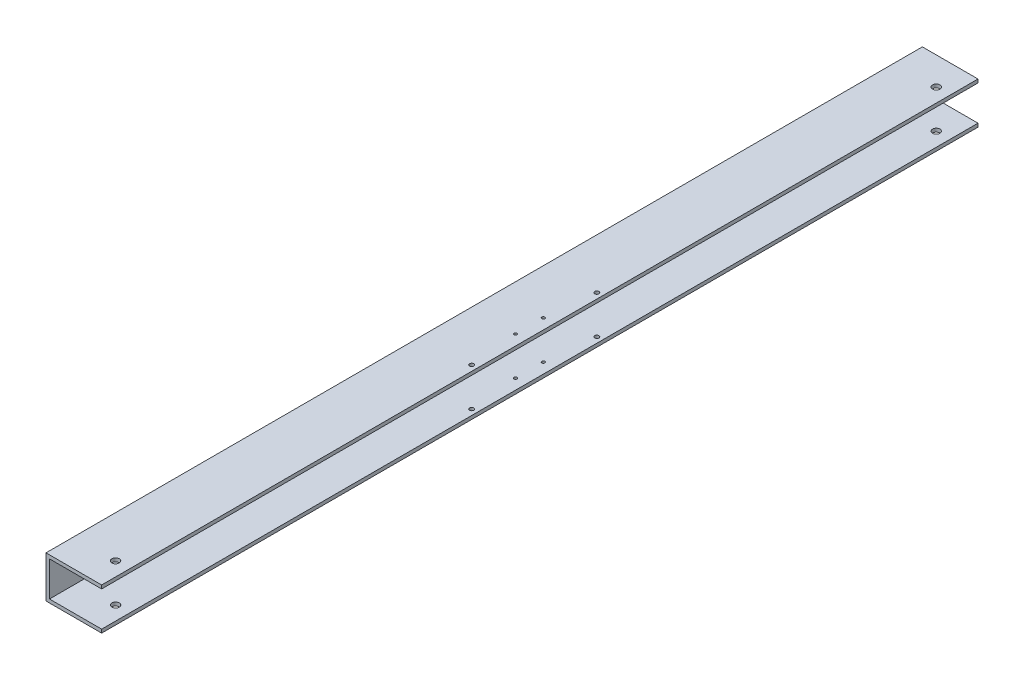
SolidWorks part; units mm, degrees
material "6061 Alloy"
ref_plane "Front Plane" through (0, 0, 0) normal (0, 0, 1) x (1, 0, 0)
ref_plane "Top Plane" through (0, 0, 0) normal (0, 1, 0) x (1, 0, 0)
ref_plane "Right Plane" through (0, 0, 0) normal (1, 0, 0) x (0, 0, -1)
sketch "Sketch1" plane through (0, 0, 0) normal (0, 0, 1) x (1, 0, 0)
  line L0 (-22.225, -15.875) -> (25.4, -15.875)
  line L1 (-25.4, 19.05) -> (25.4, 19.05)
  line L2 (-25.4, 19.05) -> (-25.4, -19.05)
  line L3 (-25.4, -19.05) -> (25.4, -19.05)
  line L4 (-22.225, 15.875) -> (-22.225, -15.875)
  line L5 (-25.4, 19.05) -> (25.4, -19.05) construction
  line L6 (-25.4, -19.05) -> (25.4, 19.05) construction
  line L7 (-22.225, 15.875) -> (25.4, 15.875)
  line L8 (25.4, 19.05) -> (25.4, 15.875)
  line L9 (25.4, -15.875) -> (25.4, -19.05)
  point P0 (0, 0)
  dimension "D1" = 50.8
  dimension "D2" = 38.1
  dimension "D3" = 3.175
extrude "Boss-Extrude1" add sketch "Sketch1" along normal mid plane 800.1
hole_wizard "#6-32 Tapped Hole1" positions "Sketch4" profile "Sketch3" tap size "#6-32" standard "ANSI Inch"
sketch "Sketch4" plane through (0, 19.05, 0) normal (0, 1, 0) x (1, 0, 0)
  line L0 (-25.4, 0) -> (25.4, 0) construction
  line L1 (-25.4, -400.05) -> (-25.4, 400.05) construction
  point P9 (15.875, -12.7)
  dimension "D1" = 12.7
  dimension "D2" = 41.275
sketch "Sketch3" plane through (15.875, 19.05, 12.7) normal (1, 0, 0) x (0, 0, 1)
  line L0 (0, 0) -> (0, 38.9117)
  line L1 (0, 38.9117) -> (1.3525, 38.099)
  line L2 (1.3525, 38.099) -> (1.3525, 0)
  line L5 (1.3525, 0) -> (0, 0)
  line L10 (0, 38.9117) -> (-1.3526, 38.099) construction
  line L11 (0, -6.35) -> (0, 107.95) construction
  dimension "Tap Drill Dia." = 2.7051
  dimension "Tap Drill Depth" = 38.099
  dimension "Drill Angle" = 118
cosmetic thread "Hole Thread1" parameters "D1"=17.272, "D2"=3.5052
hole_wizard "#6 Clearance Hole1" positions "Sketch6" profile "Sketch5" hole size "#6" standard "ANSI Inch"
sketch "Sketch6" plane through (0, 19.05, 0) normal (0, 1, 0) x (1, 0, 0)
  line L0 (25.4, 0) -> (-25.4, 0) construction
  line L1 (25.4, -400.05) -> (25.4, 400.05) construction
  line L2 (-25.4, -400.05) -> (-25.4, 400.05) construction
  point P9 (20.32, -57.15)
  dimension "D1" = 5.08
  dimension "D2" = 57.15
sketch "Sketch5" plane through (20.32, 19.05, 57.15) normal (1, 0, 0) x (0, 0, 1)
  line L0 (0, 0) -> (0, 39.2398)
  line L1 (0, 39.2398) -> (1.8986, 38.099)
  line L2 (1.8986, 38.099) -> (1.8986, 0)
  line L5 (1.8986, 0) -> (0, 0)
  line L10 (0, 39.2398) -> (-1.8987, 38.099) construction
  line L11 (0, -6.35) -> (0, 107.95) construction
  dimension "Hole Dia." = 3.7973
  dimension "Hole Depth" = 38.099
  dimension "Drill Angle" = 118
hole_wizard "1/4 Clearance Hole1" positions "Sketch8" profile "Sketch7" hole size "1/4" standard "ANSI Inch"
sketch "Sketch8" plane through (0, -19.05, 0) normal (0, -1, 0) x (-1, 0, 0)
  line L0 (-25.4, -400.05) -> (-25.4, 400.05) construction
  line L1 (25.4, -400.05) -> (-25.4, -400.05) construction
  point P0 (-12.7, -374.65)
  dimension "D1" = 12.7
  dimension "D2" = 25.4
sketch "Sketch7" plane through (12.7, -19.05, 374.65) normal (1, 0, 0) x (0, 0, -1)
  line L0 (0, 0) -> (0, 3.175)
  line L1 (0, 3.175) -> (3.3782, 3.175)
  line L2 (3.3782, 3.175) -> (3.3782, 0)
  line L5 (3.3782, 0) -> (0, 0)
  line L11 (0, -6.35) -> (0, 107.95) construction
  dimension "Thru Hole Dia." = 6.7564
  dimension "Thru Hole Depth" = 3.175
mirror "Mirror2" about plane through (0, 0, 0) normal (0, 1, 0) of "1/4 Clearance Hole1"
mirror "Mirror3" about plane through (0, 0, 0) normal (0, 0, 1) of "Mirror2", "1/4 Clearance Hole1"
mirror "Mirror4" about plane through (0, 0, 0) normal (0, 0, 1) of "#6 Clearance Hole1", "#6-32 Tapped Hole1"
